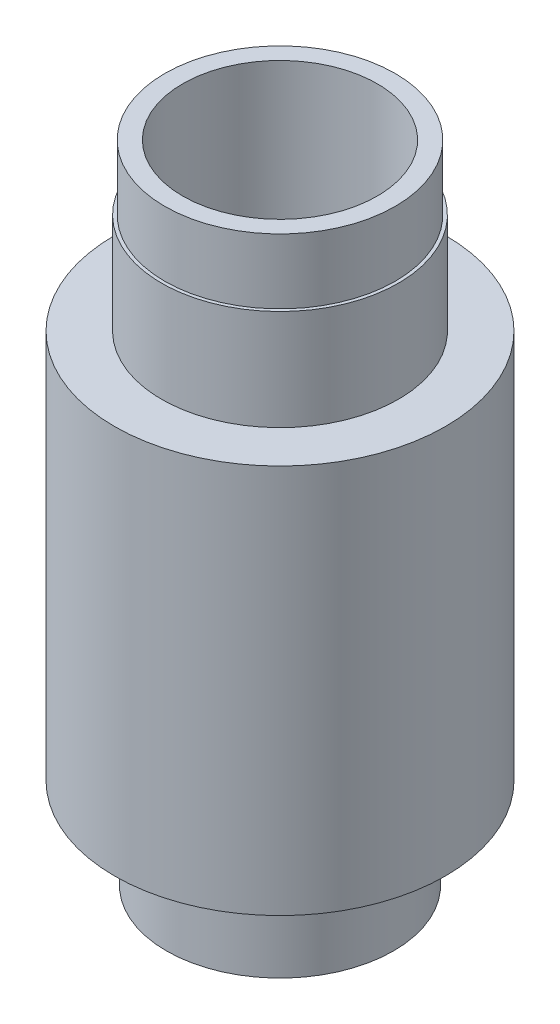
SolidWorks part; units mm, degrees
ref_plane "Front Plane" through (0, 0, 0) normal (0, 0, 1) x (1, 0, 0)
ref_plane "Top Plane" through (0, 0, 0) normal (0, 1, 0) x (1, 0, 0)
ref_plane "Right Plane" through (0, 0, 0) normal (1, 0, 0) x (0, 0, -1)
sketch "Sketch1" plane through (0, 0, 0) normal (0, 0, 1) x (1, 0, 0)
  line L0 (0, 0) -> (0, 69.209) construction
  line L1 (5.1, 0) -> (5.1, 73.2031) construction
  line L2 (0, 0) -> (3.5, 0)
  line L3 (3.5, 0) -> (3.5, 2.8)
  line L4 (3.5, 2.8) -> (5.1, 2.8)
  line L5 (5.1, 2.8) -> (5.1, 14.8)
  line L6 (5.1, 14.8) -> (3.65, 14.8)
  line L7 (3.65, 14.8) -> (3.65, 17.9)
  line L8 (3.65, 17.9) -> (3.55, 17.9)
  line L9 (3.55, 17.9) -> (3.55, 19.9)
  line L10 (3.55, 19.9) -> (0, 19.9)
  line L11 (0, 19.9) -> (0, 0)
  dimension "D1" = 5.1
  dimension "D2" = 3.5
  dimension "D3" = 2.8
  dimension "D4" = 12
  dimension "D5" = 3.1
  dimension "D6" = 7.3
  dimension "D7" = 2
  dimension "D8" = 7.1
revolve "Revolve1" add sketch "Sketch1" angle 360 about L0
sketch "Sketch3" plane through (0, 19.9, 0) normal (0, 1, 0) x (1, 0, 0)
  circle A0 centre (0, 0) radius 3
  dimension "D1" = 6
extrude "Cut-Extrude1" cut sketch "Sketch3" against normal blind 5
